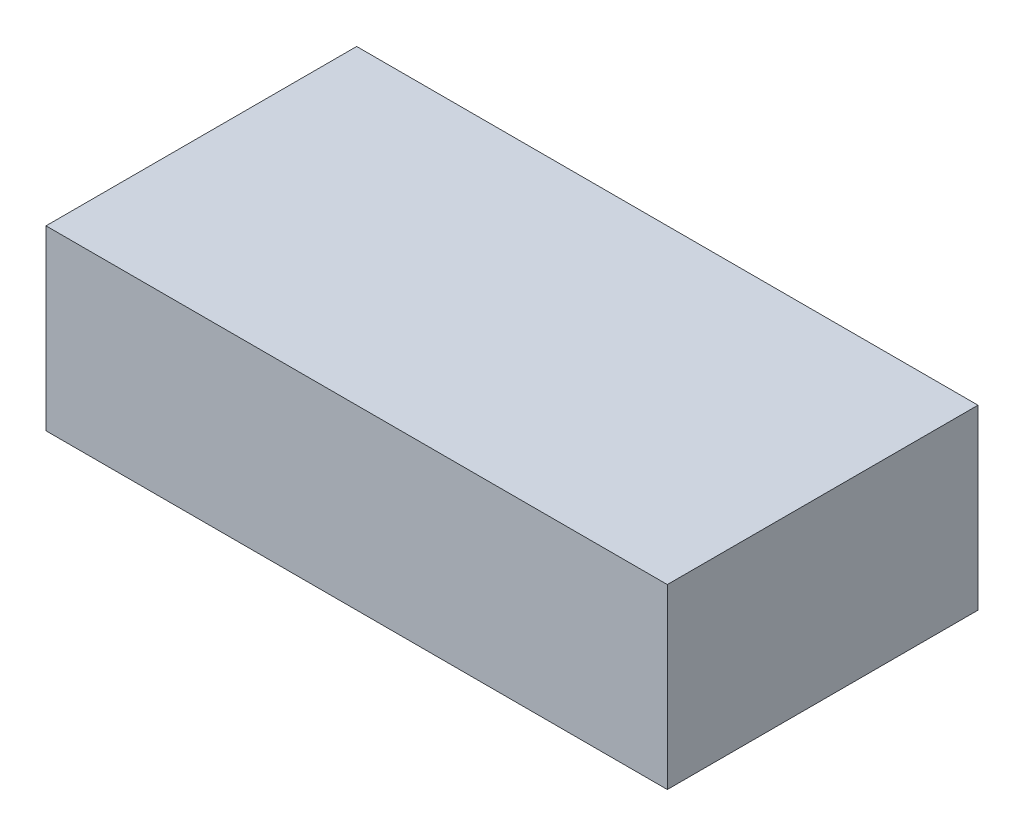
SolidWorks part; units mm, degrees
material "cardboard"
ref_plane "Front Plane" through (0, 0, 0) normal (0, 0, 1) x (1, 0, 0)
ref_plane "Top Plane" through (0, 0, 0) normal (0, 1, 0) x (1, 0, 0)
ref_plane "Right Plane" through (0, 0, 0) normal (1, 0, 0) x (0, 0, -1)
sketch "Sketch1" plane through (0, 0, 0) normal (0, 1, 0) x (1, 0, 0)
  line L1 (0, 0) -> (70, 0)
  line L2 (0, 0) -> (0, 35)
  line L3 (0, 35) -> (70, 35)
  line L4 (70, 0) -> (70, 35)
  dimension "D1" = 35
  dimension "D2" = 70
extrude "Boss-Extrude1" add sketch "Sketch1" along normal blind 20
